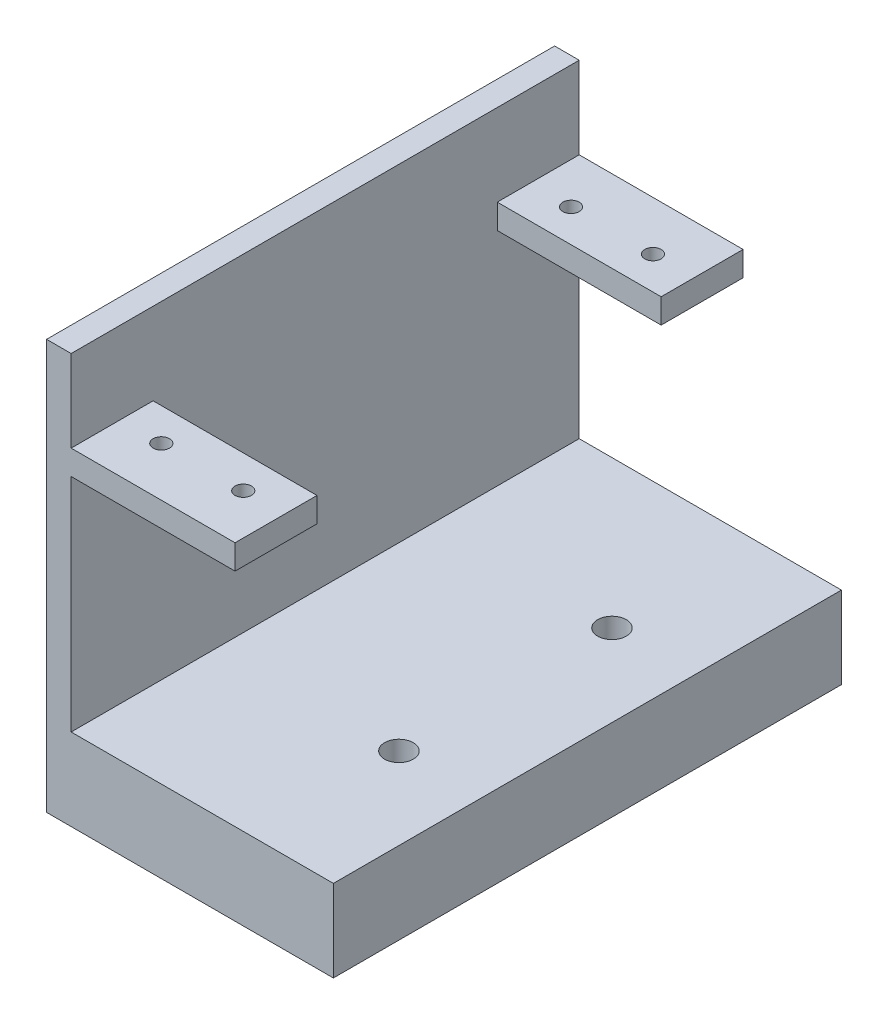
SolidWorks part; units mm, degrees
ref_plane "前视基准面" through (0, 0, 0) normal (0, 0, 1) x (1, 0, 0)
ref_plane "上视基准面" through (0, 0, 0) normal (0, 1, 0) x (1, 0, 0)
ref_plane "右视基准面" through (0, 0, 0) normal (1, 0, 0) x (0, 0, -1)
ref_plane "基准面1" through (0, 0, 0) normal (-1, 0, 0) x (0, -1, 0)
sketch "草图1" plane through (0, 0, 0) normal (-1, 0, 0) x (0, -1, 0)
  line L0 (0, 62) -> (-50, 62)
  line L1 (-50, 62) -> (-50, 0)
  line L2 (-50, 0) -> (0, 0)
  line L3 (0, 0) -> (0, 62)
extrude "凸台-拉伸1" add sketch "草图1" against normal blind 35
sketch "草图2" plane through (0, 0, 0) normal (0, 0, -1) x (-1, 0, 0)
  line L0 (-35, 10) -> (-3, 10)
  line L1 (-3, 10) -> (-3, 50)
  line L2 (-3, 50) -> (-35, 50)
  line L3 (-35, 50) -> (-35, 10)
extrude "切除-拉伸1" cut sketch "草图2" against normal through all
sketch "草图3" plane through (3, 0, 0) normal (1, 0, 0) x (0, 0, -1)
  line L0 (-10, 37) -> (-10, 40)
  line L1 (-10, 40) -> (0, 40)
  line L2 (0, 40) -> (0, 37)
  line L3 (0, 37) -> (-10, 37)
extrude "凸台-拉伸2" add sketch "草图3" along normal blind 20
sketch "草图4" plane through (3, 0, 0) normal (1, 0, 0) x (0, 0, -1)
  line L0 (-52, 40) -> (-52, 37)
  line L1 (-52, 37) -> (-62, 37)
  line L2 (-62, 37) -> (-62, 40)
  line L3 (-62, 40) -> (-52, 40)
extrude "凸台-拉伸3" add sketch "草图4" along normal blind 20
hole_wizard "Ø2.0 (2) 直径孔1" positions "草图6" profile "草图5" hole size "Ø2.0" standard "ANSI Metric"
sketch "草图6" plane through (0, 37, 0) normal (0, -1, 0) x (-1, 0, 0)
  point P0 (-8, -6)
  point P1 (-18, -6)
  point P2 (-8, -56)
  point P3 (-18, -56)
sketch "草图5" plane through (8, 37, 6) normal (1, 0, 0) x (0, 0, -1)
  line L0 (0, 0) -> (0, 13)
  line L1 (0, 13) -> (1, 13)
  line L2 (1, 13) -> (1, 0)
  line L5 (1, 0) -> (0, 0)
  line L11 (0, -6.35) -> (0, 107.95) construction
  dimension "通孔孔直径" = 2
  dimension "通孔孔深度" = 13
hole_wizard "Ø3.5 (3.5) 直径孔1" positions "草图8" profile "草图7" hole size "Ø3.5" standard "ANSI Metric"
sketch "草图8" plane through (0, 10, 0) normal (0, 1, 0) x (1, 0, 0)
  point P0 (25, -18)
  point P1 (25, -44)
sketch "草图7" plane through (25, 10, 18) normal (1, 0, 0) x (0, 0, 1)
  line L0 (0, 0) -> (0, 10)
  line L1 (0, 10) -> (1.75, 10)
  line L2 (1.75, 10) -> (1.75, 0)
  line L5 (1.75, 0) -> (0, 0)
  line L11 (0, -6.35) -> (0, 107.95) construction
  dimension "通孔孔直径" = 3.5
  dimension "通孔孔深度" = 10
